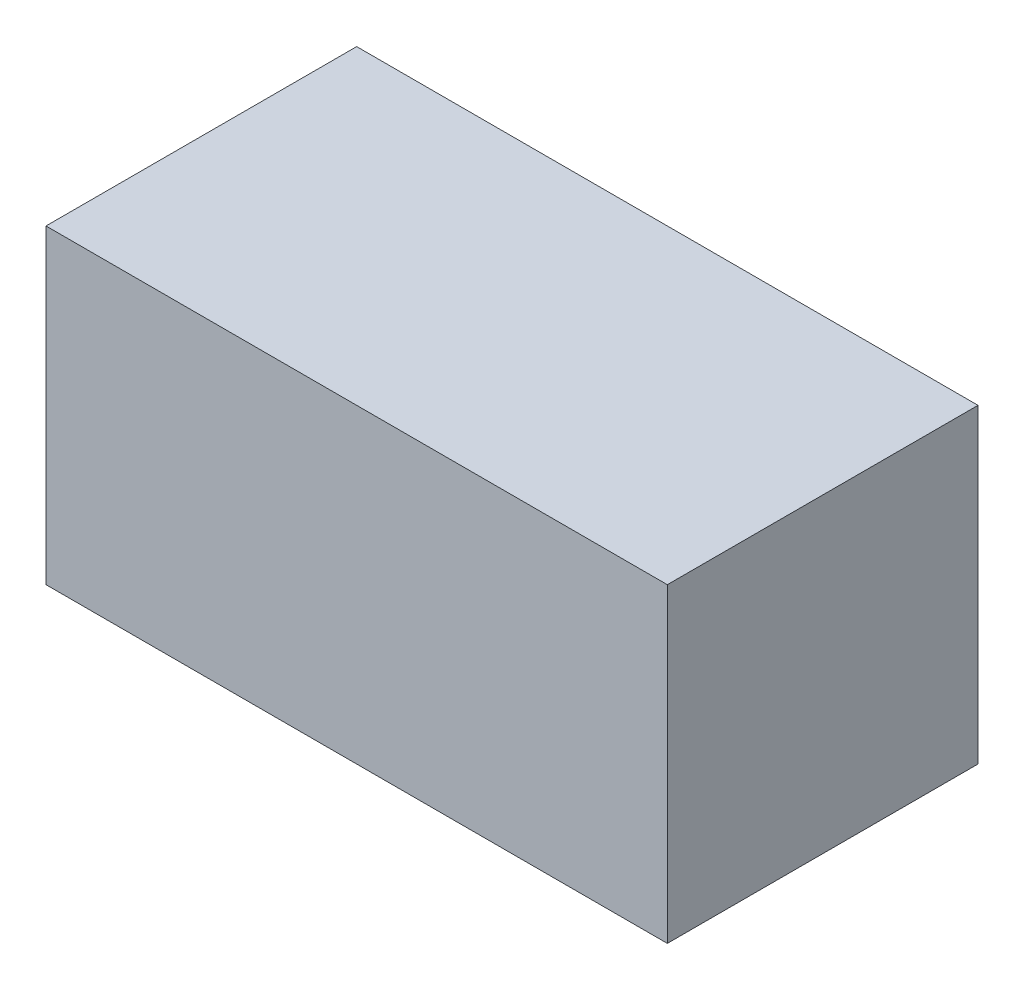
SolidWorks part; units mm, degrees
ref_plane "前视基准面" through (0, 0, 0) normal (0, 0, 1) x (1, 0, 0)
ref_plane "上视基准面" through (0, 0, 0) normal (0, 1, 0) x (1, 0, 0)
ref_plane "右视基准面" through (0, 0, 0) normal (1, 0, 0) x (0, 0, -1)
sketch "草图1" plane through (0, 0, 0) normal (0, 0, 1) x (1, 0, 0)
  line L0 (-2.0102, 2.0478) -> (-0.0102, 2.0478)
  line L5 (-0.0102, 2.0478) -> (-0.0102, 1.0478)
  line L6 (-0.0102, 1.0478) -> (-2.0102, 1.0478)
  line L7 (-2.0102, 1.0478) -> (-2.0102, 2.0478)
extrude "凸台-拉伸1" add sketch "草图1" along normal blind 1
